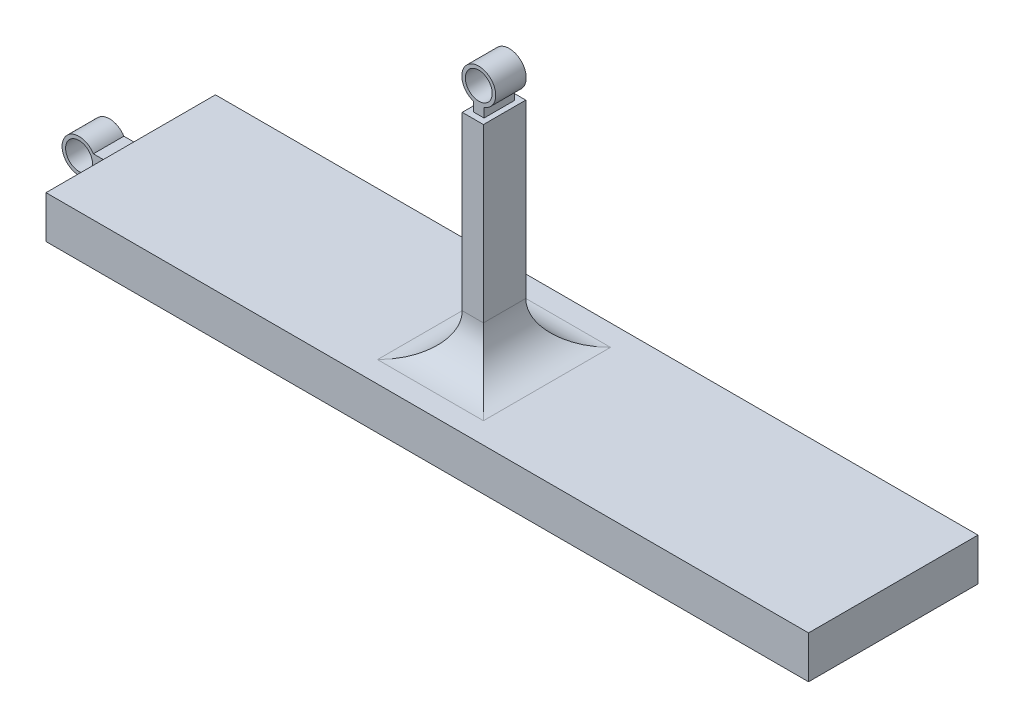
SolidWorks part; units mm, degrees
ref_plane "Front Plane" through (0, 0, 0) normal (0, 0, 1) x (1, 0, 0)
ref_plane "Top Plane" through (0, 0, 0) normal (0, 1, 0) x (1, 0, 0)
ref_plane "Right Plane" through (0, 0, 0) normal (1, 0, 0) x (0, 0, -1)
sketch "Sketch1" plane through (0, 0, 0) normal (0, 0, 1) x (1, 0, 0)
  line L0 (-79.455, -1.7658) -> (820.545, -1.7658)
  line L1 (-79.455, -1.7658) -> (-79.455, -51.7658)
  line L2 (-79.455, -51.7658) -> (820.545, -51.7658)
  line L3 (820.545, -51.7658) -> (820.545, -1.7658)
extrude "Boss-Extrude1" add sketch "Sketch1" along normal blind 200
sketch "Sketch2" plane through (-79.455, 0, 0) normal (-1, 0, 0) x (0, 0, 1)
  line L0 (100, -51.7658) -> (100, -1.7658) construction
  line L3 (200, -51.7658) -> (0, -51.7658) construction
  line L4 (200, -1.7658) -> (0, -1.7658) construction
  line L5 (0, -26.7658) -> (200, -26.7658) construction
  line L6 (0, -1.7658) -> (0, -51.7658) construction
  line L7 (200, -1.7658) -> (200, -51.7658) construction
sketch "Sketch4" plane through (0, 0, 0) normal (0, 0, -1) x (-1, 0, 0)
  line L1 (79.455, -51.7658) -> (79.455, -1.7658) construction
  line L2 (79.455, -26.7658) -> (79.455, -16.1051)
  line L3 (79.455, -16.1051) -> (105.5331, -16.1051)
  line L4 (79.455, -26.7658) -> (79.455, -39.5393)
  line L5 (79.455, -39.5393) -> (107.0654, -39.5393)
  circle A0 centre (122.455, -26.7658) radius 20
  circle A1 centre (122.455, -26.7658) radius 15.875
  line M5 (79.455, -51.7658) -> (79.455, -1.7658)
  dimension "D1" = 43
extrude "Boss-Extrude2" add sketch "Sketch4" against normal blind 36 from offset 82 contours A0 L3 L5 M5 | A0 A1 offset against normal yes
sketch "Sketch5" plane through (0, -1.7658, 0) normal (0, 1, 0) x (1, 0, 0)
  line L0 (-79.455, -100) -> (336.815, -100)
  line L1 (-79.455, 0) -> (-79.455, -200) construction
  dimension "D1" = 416.27
ref_plane "Plane1" through (336.815, 0, 0) normal (1, 0, 0) x (0, 0, -1)
ref_plane "Plane2" through (0, 0, 100) normal (0, 0, 1) x (1, 0, 0)
sketch "Sketch8" plane through (0, 0, 100) normal (0, 0, 1) x (1, 0, 0)
  line L0 (336.815, -1.7658) -> (336.815, 250.9842)
  line L1 (-79.455, -1.7658) -> (336.815, -1.7658) construction
  line L2 (336.815, -110) -> (336.815, 110) construction
  line L3 (336.815, -1.7658) -> (361.815, -1.7658)
  line L4 (820.545, -1.7658) -> (-79.455, -1.7658) construction
  line L5 (361.815, -1.7658) -> (361.815, 250.9842)
  line L6 (361.815, 250.9842) -> (336.815, 250.9842)
extrude "Boss-Extrude3" add sketch "Sketch8" along normal mid plane 50
fillet "Fillet1" radius 50 4 edges at (336.815, -1.7658, 100) (349.315, -1.7658, 125) (361.815, -1.7658, 100) (349.315, -1.7658, 75)
sketch "Sketch9" plane through (0, 0, 100) normal (0, 0, 1) x (1, 0, 0)
  line L0 (349.315, 250.9842) -> (349.315, 280.9842)
  line L1 (361.815, 250.9842) -> (336.815, 250.9842) construction
  line L2 (349.315, 250.9842) -> (355.5642, 250.9842)
  line L3 (355.5642, 250.9842) -> (355.5642, 261.9856)
  line L4 (349.315, 250.9842) -> (343.3973, 250.9842)
  line L5 (343.3973, 250.9842) -> (343.3973, 261.8797)
  circle A0 centre (349.315, 280.9842) radius 20
  circle A1 centre (349.315, 280.9842) radius 15.875
  dimension "D1" = 30
extrude "Boss-Extrude4" add sketch "Sketch9" along normal mid plane 36
